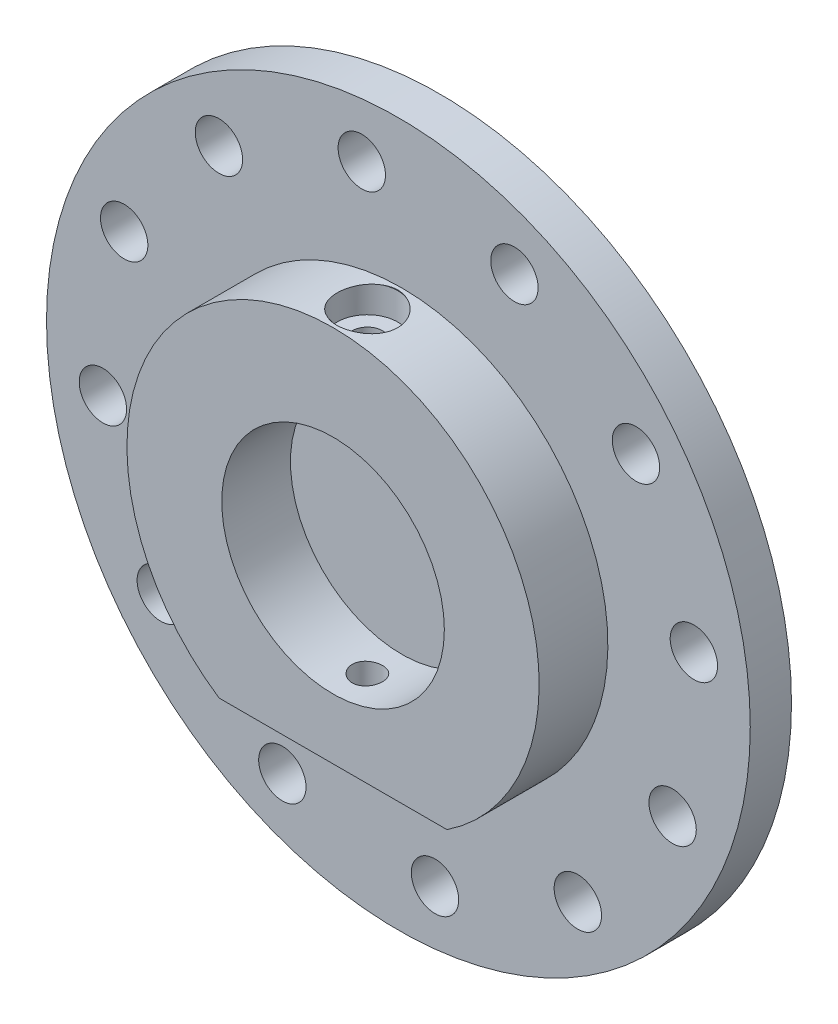
SolidWorks part; units mm, degrees
ref_plane "Front Plane" through (0, 0, 0) normal (0, 0, 1) x (1, 0, 0)
ref_plane "Top Plane" through (0, 0, 0) normal (0, 1, 0) x (1, 0, 0)
ref_plane "Right Plane" through (0, 0, 0) normal (1, 0, 0) x (0, 0, -1)
sketch "Sketch1" plane through (0, 0, 0) normal (0, 0, 1) x (1, 0, 0)
  circle A0 centre (-0.2449, 0) radius 25.6087
  arc A1 (-18.8411, 7.3851) -> (-21.56, 9.5045) centre (-20.2006, 8.4448) ccw
  arc A2 (-21.56, 9.5045) -> (-18.8411, 7.3851) centre (-20.2006, 8.4448) ccw
  arc A3 (-20.39, -3.7241) -> (-23.1088, -1.6047) centre (-21.7494, -2.6644) ccw
  arc A4 (-23.1088, -1.6047) -> (-20.39, -3.7241) centre (-21.7494, -2.6644) ccw
  arc A5 (-16.1767, -14.1194) -> (-18.8956, -12) centre (-17.5361, -13.0597) ccw
  arc A6 (-18.8956, -12) -> (-16.1767, -14.1194) centre (-17.5361, -13.0597) ccw
  arc A7 (-7.3303, -21.0154) -> (-10.0491, -18.896) centre (-8.6897, -19.9557) ccw
  arc A8 (-10.0491, -18.896) -> (-7.3303, -21.0154) centre (-8.6897, -19.9557) ccw
  arc A9 (3.7789, -22.5642) -> (1.0601, -20.4448) centre (2.4195, -21.5045) ccw
  arc A10 (1.0601, -20.4448) -> (3.7789, -22.5642) centre (2.4195, -21.5045) ccw
  arc A11 (11.4554, -16.2315) -> (14.1742, -18.3509) centre (12.8148, -17.2912) ccw
  arc A12 (14.1742, -18.3509) -> (11.4554, -16.2315) centre (12.8148, -17.2912) ccw
  arc A13 (18.3513, -7.3851) -> (21.0702, -9.5045) centre (19.7108, -8.4448) ccw
  arc A14 (21.0702, -9.5045) -> (18.3513, -7.3851) centre (19.7108, -8.4448) ccw
  arc A15 (22.619, 1.6047) -> (19.9002, 3.7241) centre (21.2596, 2.6644) ccw
  arc A16 (19.9002, 3.7241) -> (22.619, 1.6047) centre (21.2596, 2.6644) ccw
  arc A17 (15.6869, 14.1194) -> (18.4058, 12) centre (17.0463, 13.0597) ccw
  arc A18 (18.4058, 12) -> (15.6869, 14.1194) centre (17.0463, 13.0597) ccw
  arc A19 (6.8405, 21.0154) -> (9.5593, 18.896) centre (8.1999, 19.9557) ccw
  arc A20 (9.5593, 18.896) -> (6.8405, 21.0154) centre (8.1999, 19.9557) ccw
  arc A21 (-4.2687, 22.5642) -> (-1.5499, 20.4448) centre (-2.9093, 21.5045) ccw
  arc A22 (-1.5499, 20.4448) -> (-4.2687, 22.5642) centre (-2.9093, 21.5045) ccw
  arc A23 (-14.664, 18.3509) -> (-11.9452, 16.2315) centre (-13.3046, 17.2912) ccw
  arc A24 (-11.9452, 16.2315) -> (-14.664, 18.3509) centre (-13.3046, 17.2912) ccw
extrude "Boss-Extrude1" add sketch "Sketch1" along normal blind 3
sketch "Sketch2" plane through (0, 0, 3) normal (0, 0, 1) x (1, 0, 0)
  line L0 (0, 0) -> (0, -12.5) construction
  line L1 (8.2916, -12.5) -> (-8.2916, -12.5)
  arc A1 (8.2916, -12.5) -> (-8.2916, -12.5) centre (0, 0) ccw
  circle A3 centre (0, 0) radius 8.1
  dimension "D1" = 16.2
  dimension "D2" = 12.5
extrude "Boss-Extrude2" add sketch "Sketch2" along normal blind 5
ref_plane "Plane1" through (0, 15, 0) normal (0, 1, 0) x (1, 0, 0)
sketch "Sketch3" plane through (0, 15, 0) normal (0, 1, 0) x (1, 0, 0)
  line L0 (0, -3) -> (0, -8) construction
  line L1 (-15, -3) -> (15, -3) construction
  line L2 (-15, -8) -> (15, -8) construction
  circle A0 centre (0, -5.5) radius 1
  point P6 (0, -5.5)
hole_wizard "CBORE for M2 SHCS1" positions "Sketch3" profile "Sketch4" counterbore size "M2" standard "ANSI Metric" end condition through all
sketch "Sketch4" plane through (0, 15, 5.5) normal (1, 0, 0) x (0, 0, 1)
  line L0 (0, 0) -> (0, 40.6087)
  line L1 (0, 40.6087) -> (1.1, 40.6087)
  line L3 (1.1, 40.6087) -> (1.1, 2)
  line L4 (2.2, 2) -> (1.1, 2)
  line L5 (2.2, 2) -> (2.2, 0.025)
  line L6 (2.2, 0.025) -> (2.225, 0)
  line L7 (2.225, 0) -> (0, 0)
  line L8 (-2.2, 0.025) -> (-2.225, 0) construction
  line L11 (0, -6.35) -> (0, 107.95) construction
  dimension "Thru Hole Dia." = 2.2
  dimension "Thru Hole Depth" = 40.6087
  dimension "C'Bore Dia." = 4.4
  dimension "C'Bore Depth" = 2
  dimension "Near C'Sink Dia." = 4.45
  dimension "Near C'Sink Angle" = 90
sketch "Sketch6" plane through (0, 0, 8) normal (0, 0, 1) x (1, 0, 0)
  line L0 (0, 0) -> (0, -12.5) construction
  line L1 (8.2916, -12.5) -> (-8.2916, -12.5)
  circle A0 centre (0, 0) radius 15 construction
  arc A1 (-8.2916, -12.5) -> (8.2916, -12.5) centre (0, 0) ccw
  dimension "D1" = 12.5
